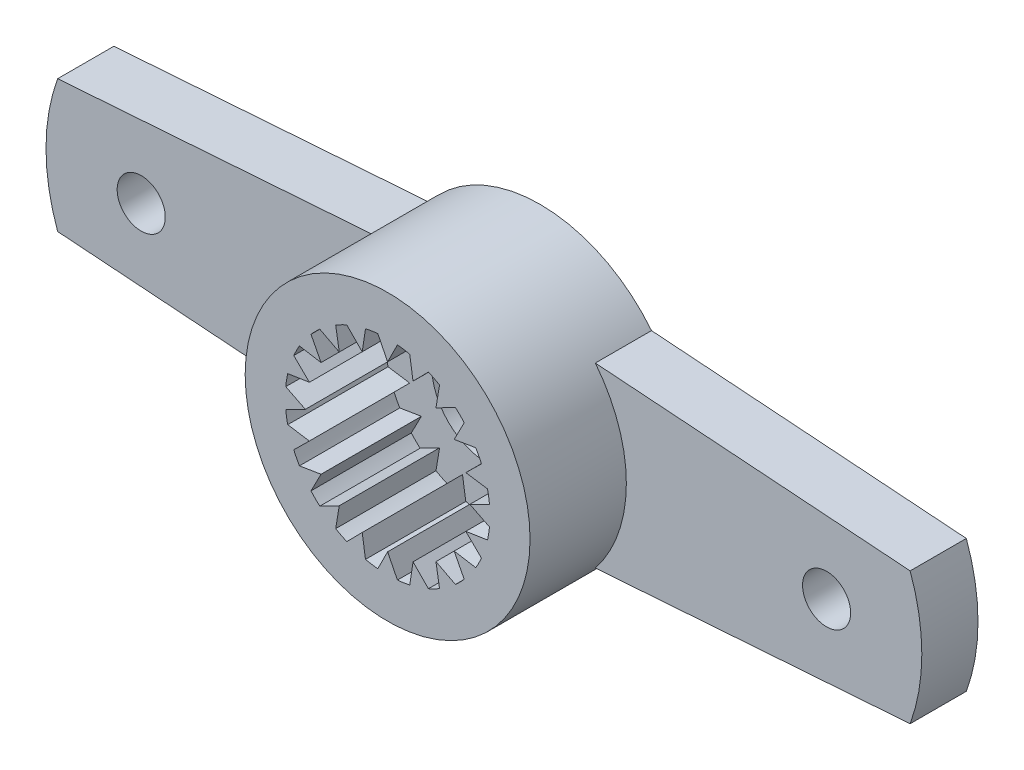
SolidWorks part; units mm, degrees
ref_plane "Front Plane" through (0, 0, 0) normal (0, 0, 1) x (1, 0, 0)
ref_plane "Top Plane" through (0, 0, 0) normal (0, 1, 0) x (1, 0, 0)
ref_plane "Right Plane" through (0, 0, 0) normal (1, 0, 0) x (0, 0, -1)
sketch "Sketch2" plane through (0, 0, 0) normal (0, 0, 1) x (1, 0, 0)
  circle A0 centre (0, 0) radius 3.55
  dimension "D1" = 7.1
sketch "Sketch3" plane through (0, 0, 0) normal (0, 0, 1) x (1, 0, 0)
  line L0 (-0.2447, 2.5382) -> (0, 2.05)
  line L1 (0, 2.05) -> (0.2447, 2.5382)
  line L2 (0.5516, 2.4896) -> (0.6335, 1.9497)
  line L3 (0.6335, 1.9497) -> (1.0171, 2.3384)
  line L4 (1.294, 2.1973) -> (1.205, 1.6585)
  line L5 (1.205, 1.6585) -> (1.6899, 1.9096)
  line L6 (1.9096, 1.6899) -> (1.6585, 1.205)
  line L7 (1.6585, 1.205) -> (2.1973, 1.294)
  line L8 (2.3384, 1.0171) -> (1.9497, 0.6335)
  line L9 (1.9497, 0.6335) -> (2.4896, 0.5516)
  line L10 (2.5382, 0.2447) -> (2.05, 0)
  line L11 (2.05, 0) -> (2.5382, -0.2447)
  line L12 (2.4896, -0.5516) -> (1.9497, -0.6335)
  line L13 (1.9497, -0.6335) -> (2.3384, -1.0171)
  line L14 (2.1973, -1.294) -> (1.6585, -1.205)
  line L15 (1.6585, -1.205) -> (1.9096, -1.6899)
  line L16 (1.6899, -1.9096) -> (1.205, -1.6585)
  line L17 (1.205, -1.6585) -> (1.294, -2.1973)
  line L18 (1.0171, -2.3384) -> (0.6335, -1.9497)
  line L19 (0.6335, -1.9497) -> (0.5516, -2.4896)
  line L20 (0.2447, -2.5382) -> (0, -2.05)
  line L21 (0, -2.05) -> (-0.2447, -2.5382)
  line L22 (-0.5516, -2.4896) -> (-0.6335, -1.9497)
  line L23 (-0.6335, -1.9497) -> (-1.0171, -2.3384)
  line L24 (-1.294, -2.1973) -> (-1.205, -1.6585)
  line L25 (-1.205, -1.6585) -> (-1.6899, -1.9096)
  line L26 (-1.9096, -1.6899) -> (-1.6585, -1.205)
  line L27 (-1.6585, -1.205) -> (-2.1973, -1.294)
  line L28 (-2.3384, -1.0171) -> (-1.9497, -0.6335)
  line L29 (-1.9497, -0.6335) -> (-2.4896, -0.5516)
  line L30 (-2.5382, -0.2447) -> (-2.05, 0)
  line L31 (-2.05, 0) -> (-2.5382, 0.2447)
  line L32 (-2.4896, 0.5516) -> (-1.9497, 0.6335)
  line L33 (-1.9497, 0.6335) -> (-2.3384, 1.0171)
  line L34 (-2.1973, 1.294) -> (-1.6585, 1.205)
  line L35 (-1.6585, 1.205) -> (-1.9096, 1.6899)
  line L36 (-1.6899, 1.9096) -> (-1.205, 1.6585)
  line L37 (-1.205, 1.6585) -> (-1.294, 2.1973)
  line L38 (-1.0171, 2.3384) -> (-0.6335, 1.9497)
  line L39 (-0.6335, 1.9497) -> (-0.5516, 2.4896)
  arc A0 (-0.2447, 2.5382) -> (0.2447, 2.5382) centre (0, 0) cw
  arc A2 (0.5516, 2.4896) -> (1.0171, 2.3384) centre (0, 0) cw
  arc A3 (1.294, 2.1973) -> (1.6899, 1.9096) centre (0, 0) cw
  arc A4 (1.9096, 1.6899) -> (2.1973, 1.294) centre (0, 0) cw
  arc A5 (2.3384, 1.0171) -> (2.4896, 0.5516) centre (0, 0) cw
  arc A6 (2.5382, 0.2447) -> (2.5382, -0.2447) centre (0, 0) cw
  arc A7 (2.4896, -0.5516) -> (2.3384, -1.0171) centre (0, 0) cw
  arc A8 (2.1973, -1.294) -> (1.9096, -1.6899) centre (0, 0) cw
  arc A9 (1.6899, -1.9096) -> (1.294, -2.1973) centre (0, 0) cw
  arc A10 (1.0171, -2.3384) -> (0.5516, -2.4896) centre (0, 0) cw
  arc A11 (0.2447, -2.5382) -> (-0.2447, -2.5382) centre (0, 0) cw
  arc A12 (-0.5516, -2.4896) -> (-1.0171, -2.3384) centre (0, 0) cw
  arc A13 (-1.294, -2.1973) -> (-1.6899, -1.9096) centre (0, 0) cw
  arc A14 (-1.9096, -1.6899) -> (-2.1973, -1.294) centre (0, 0) cw
  arc A15 (-2.3384, -1.0171) -> (-2.4896, -0.5516) centre (0, 0) cw
  arc A16 (-2.5382, -0.2447) -> (-2.5382, 0.2447) centre (0, 0) cw
  arc A17 (-2.4896, 0.5516) -> (-2.3384, 1.0171) centre (0, 0) cw
  arc A18 (-2.1973, 1.294) -> (-1.9096, 1.6899) centre (0, 0) cw
  arc A19 (-1.6899, 1.9096) -> (-1.294, 2.1973) centre (0, 0) cw
  arc A20 (-1.0171, 2.3384) -> (-0.5516, 2.4896) centre (0, 0) cw
  point P66 (0, 0)
  dimension "D1" = 20
ref_plane "Plane1" through (0, 0, -2.4) normal (0, 0, 1) x (1, 0, 0)
sketch "Sketch4" plane through (0, 0, -2.4) normal (0, 0, 1) x (1, 0, 0)
  line L0 (2.7764, 2.2123) -> (10.6226, 1.65)
  line L1 (2.7764, -2.2123) -> (10.6226, -1.65)
  arc A0 (10.6226, 1.65) -> (10.6226, -1.65) centre (6.0891, 0) cw
  arc A1 (2.7764, 2.2123) -> (2.7764, -2.2123) centre (0, 0) cw
extrude "Boss-Extrude1" add sketch "Sketch2" against normal blind 3.8 contours A0
extrude "Boss-Extrude2" add sketch "Sketch4" against normal blind 1.4
sketch "Sketch5" plane through (0, 0, 0) normal (0, 0, 1) x (1, 0, 0)
  circle A0 centre (0, 0) radius 2.55
extrude "Cut-Extrude1" cut sketch "Sketch5" against normal blind 2.5
extrude "Boss-Extrude3" add sketch "Sketch3" against normal up to surface (2.5 mm away) up to face at (2.55, 0, -2.5)
sketch "Sketch6" plane through (0, 0, -2.5) normal (0, 0, 1) x (1, 0, 0)
  circle A0 centre (0, 0) radius 1.4
  dimension "D1" = 2.8
extrude "Cut-Extrude2" cut sketch "Sketch6" against normal through all
sketch "Sketch7" plane through (0, 0, -2.4) normal (0, 0, 1) x (1, 0, 0)
  circle A0 centre (8.5405, 0) radius 0.6
  dimension "D1" = 1.2
extrude "Cut-Extrude3" cut sketch "Sketch7" against normal through all
mirror "Mirror1" about plane through (0, 0, 0) normal (1, 0, 0) of "Boss-Extrude2"
mirror "Mirror2" about plane through (0, 0, 0) normal (1, 0, 0) of "Cut-Extrude3"
